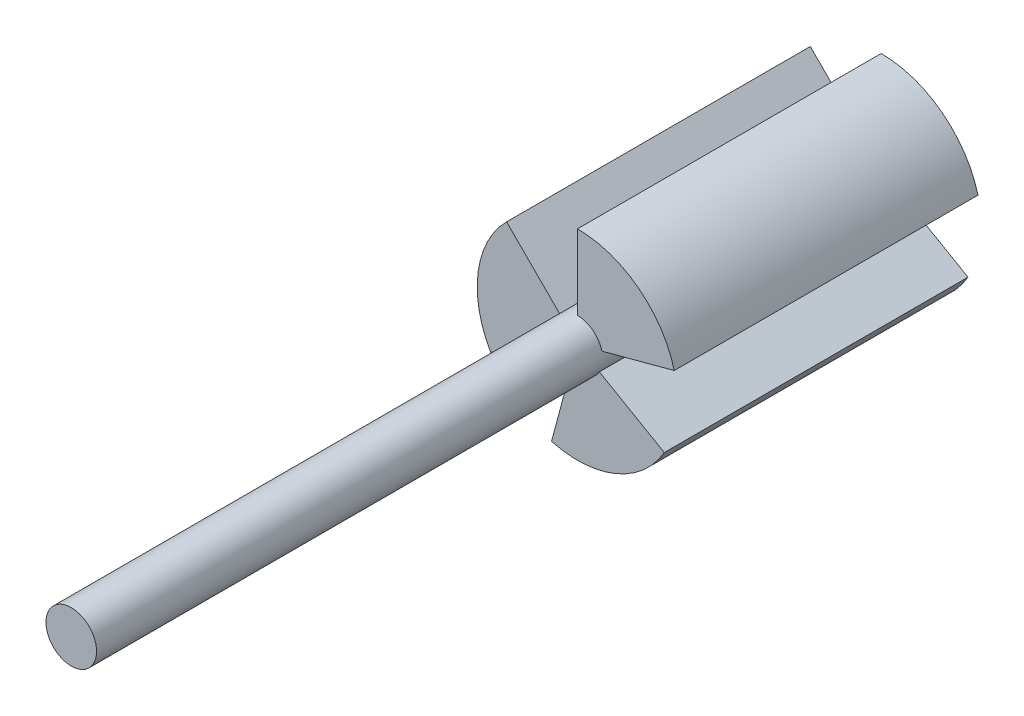
SolidWorks part; units mm, degrees
material "Copper"
ref_plane "Front Plane" through (0, 0, 0) normal (0, 0, 1) x (1, 0, 0)
ref_plane "Top Plane" through (0, 0, 0) normal (0, 1, 0) x (1, 0, 0)
ref_plane "Right Plane" through (0, 0, 0) normal (1, 0, 0) x (0, 0, -1)
sketch "Sketch1" plane through (0, 0, 0) normal (0, 0, 1) x (1, 0, 0)
  circle A0 centre (0, 0) radius 251.46
  dimension "D1" = 502.92
extrude "Boss-Extrude1" add sketch "Sketch1" along normal blind 762
sketch "Sketch2" plane through (0, 0, 762) normal (0, 0, 1) x (1, 0, 0)
  line L0 (-44.9013, 44.9013) -> (-177.8091, 177.8091)
  line L1 (0, 251.46) -> (0, 63.5)
  line L2 (61.3363, 16.435) -> (242.8917, 65.0826)
  line L3 (217.7707, -125.73) -> (54.9926, -31.75)
  line L4 (-16.435, -61.3363) -> (-65.0826, -242.8917)
  line L5 (-217.7707, -125.73) -> (-54.9926, -31.75)
  arc A0 (0, 63.5) -> (-44.9013, 44.9013) centre (0, 0) ccw construction
  circle A1 centre (0, 0) radius 251.46 construction
  arc A2 (0, 63.5) -> (-44.9013, 44.9013) centre (0, 0) ccw
  circle A3 centre (0, 0) radius 251.46
  arc A4 (0, 251.46) -> (-177.8091, 177.8091) centre (0, 0) ccw
  arc A5 (217.7707, -125.73) -> (242.8917, 65.0826) centre (0, 0) ccw
  arc A6 (54.9926, -31.75) -> (61.3363, 16.435) centre (0, 0) ccw
  arc A7 (-217.7707, -125.73) -> (-65.0826, -242.8917) centre (0, 0) ccw
  arc A8 (-54.9926, -31.75) -> (-16.435, -61.3363) centre (0, 0) ccw
  point P21 (0, 0)
  dimension "D1" = 127
  dimension "D2" = 0
  dimension "D3" = 45
  dimension "D4" = 3
extrude "Cut-Extrude1" cut sketch "Sketch2" against normal through all
sketch "Sketch3" plane through (0, 0, 762) normal (0, 0, 1) x (1, 0, 0)
  circle A0 centre (0, 0) radius 63.5
extrude "Boss-Extrude2" add sketch "Sketch3" along normal blind 1270
